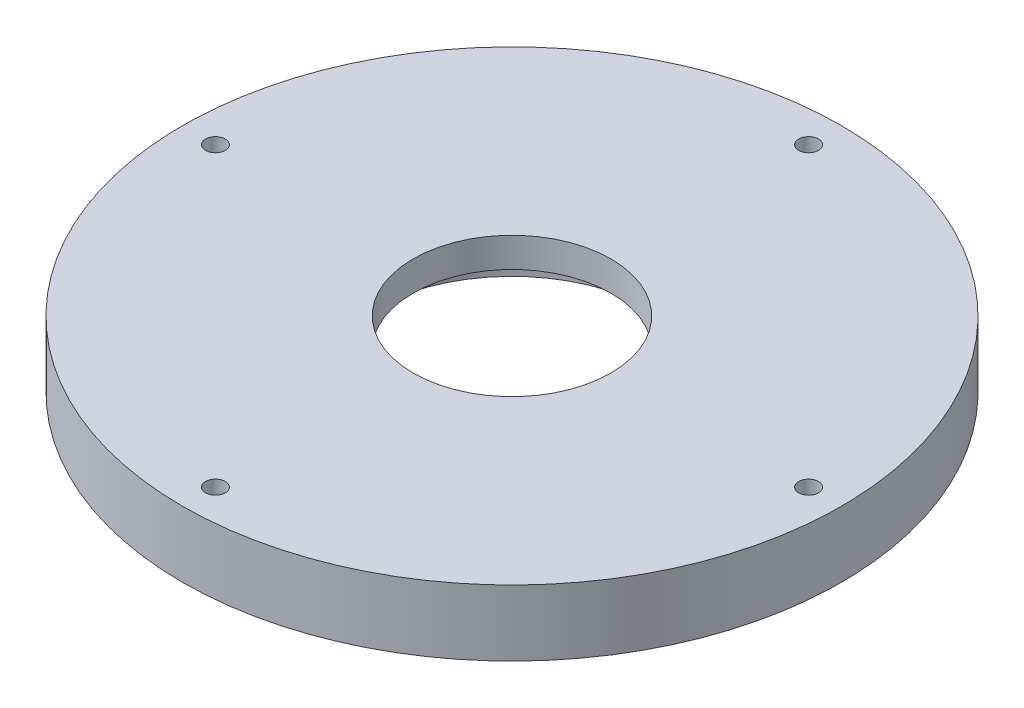
SolidWorks part; units mm, degrees
ref_plane "前视基准面" through (0, 0, 0) normal (0, 0, 1) x (1, 0, 0)
ref_plane "上视基准面" through (0, 0, 0) normal (0, 1, 0) x (1, 0, 0)
ref_plane "右视基准面" through (0, 0, 0) normal (1, 0, 0) x (0, 0, -1)
other "Configuration Table"
sketch "草图2" plane through (0, 0, 0) normal (0, 1, 0) x (1, 0, 0)
  circle A0 centre (0, 0) radius 100
  circle A1 centre (0, 0) radius 90 construction
  circle A2 centre (0, 90) radius 3
  circle A3 centre (90, 0) radius 3
  circle A4 centre (0, -90) radius 3
  circle A5 centre (-90, 0) radius 3
  circle A6 centre (0, 0) radius 30
  dimension "D1" = 4
extrude "凸台-拉伸1" add sketch "草图2" along normal blind 20
sketch "草图3" plane through (0, 0, 0) normal (0, -1, 0) x (1, 0, 0)
  circle A0 centre (0, 0) radius 43
  dimension "D1" = 86
extrude "切除-拉伸1" cut sketch "草图3" against normal blind 11
